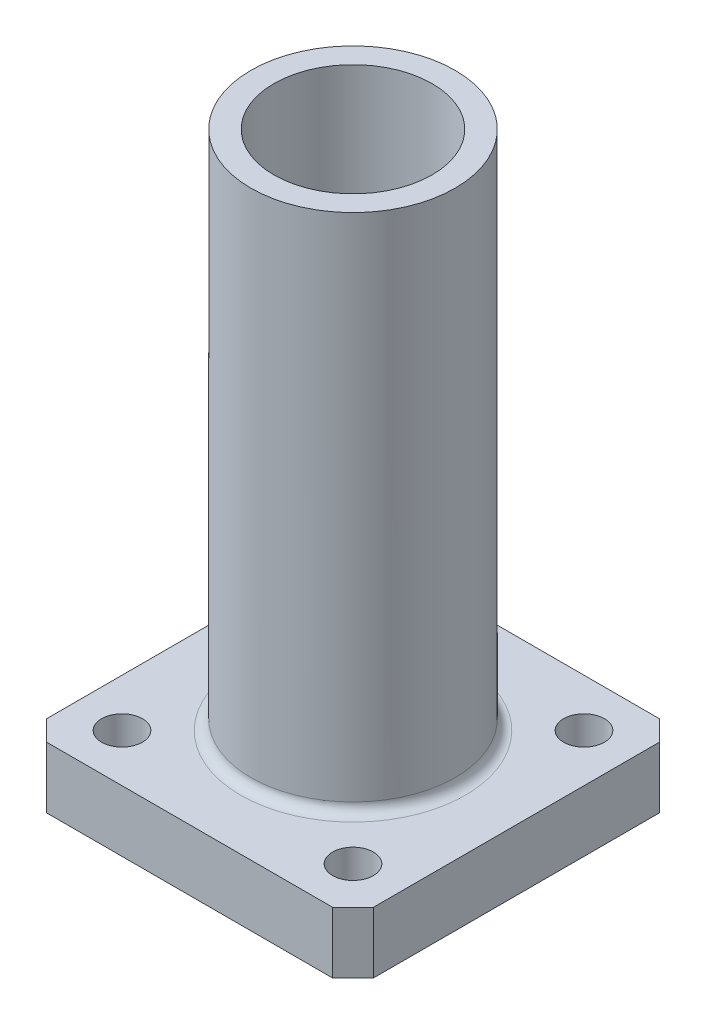
SolidWorks part; units mm, degrees
ref_plane "Front Plane" through (0, 0, 0) normal (0, 0, 1) x (1, 0, 0)
ref_plane "Top Plane" through (0, 0, 0) normal (0, 1, 0) x (1, 0, 0)
ref_plane "Right Plane" through (0, 0, 0) normal (1, 0, 0) x (0, 0, -1)
sketch "Sketch1" plane through (0, 0, 0) normal (0, 1, 0) x (1, 0, 0)
  line L0 (-16.2748, 13.4011) -> (-14.2748, 15.4011)
  line L1 (-14.2748, 15.4011) -> (13.7252, 15.4011)
  line L2 (-16.2748, 13.4011) -> (-16.2748, -14.5989)
  line L3 (-14.2748, -16.5989) -> (13.7252, -16.5989)
  line L4 (15.7252, 13.4011) -> (15.7252, -14.5989)
  line L5 (13.7252, 15.4011) -> (15.7252, 13.4011)
  line L6 (13.7252, -16.5989) -> (15.7252, -14.5989)
  line L7 (-16.2748, -14.5989) -> (-14.2748, -16.5989)
  line L8 (-14.2748, -14.5989) -> (14.7252, 14.4011) construction
  line L9 (-15.2748, 14.4011) -> (14.7252, -15.5989) construction
  circle A0 centre (-0.2748, -0.5989) radius 16 construction
  circle A1 centre (11.0389, 10.7149) radius 2
  circle A2 centre (-11.5885, 10.7149) radius 2
  circle A3 centre (-11.5885, -11.9126) radius 2
  circle A4 centre (11.0389, -11.9126) radius 2
  point P0 (-16.2748, 15.4011)
  point P1 (15.7252, -16.5989)
  point P2 (-16.2748, -16.5989)
  point P3 (15.7252, 15.4011)
  dimension "D3" = 4
  dimension "D4" = 4
  dimension "D5" = 4
  dimension "4" = 4
  dimension "D1" = 32
  dimension "D2" = 32
extrude "Boss-Extrude1" add sketch "Sketch1" along normal blind 6
sketch "Sketch2" plane through (0, 6, 0) normal (0, 1, 0) x (1, 0, 0)
  line L0 (-15.2748, 14.4011) -> (14.7252, -15.5989) construction
  circle A0 centre (-0.2748, -0.5989) radius 10
  dimension "D1" = 20
extrude "Boss-Extrude2" add sketch "Sketch2" along normal blind 51
sketch "Sketch3" plane through (0, 57, 0) normal (0, 1, 0) x (1, 0, 0)
  circle A0 centre (-0.2748, -0.5989) radius 7.75
  dimension "D1" = 15.5
extrude "Cut-Extrude1" cut sketch "Sketch3" against normal through all
fillet "Fillet1" radius 1 1 edges at (-0.2748, 6, -9.4011)
